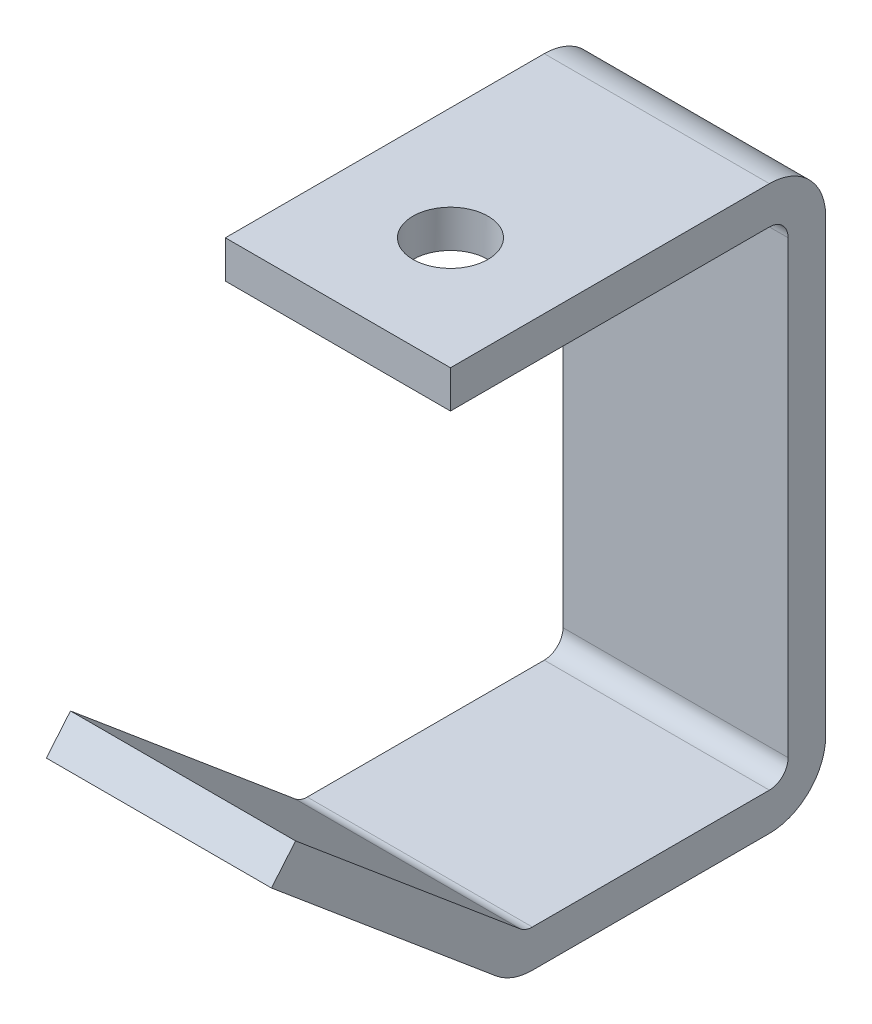
SolidWorks part; units mm, degrees
ref_plane "front" through (0, 0, 0) normal (0, 0, 1) x (1, 0, 0)
ref_plane "top" through (0, 0, 0) normal (0, 1, 0) x (1, 0, 0)
ref_plane "right" through (0, 0, 0) normal (1, 0, 0) x (0, 0, -1)
sketch "Sketch1" plane through (0, 0, 0) normal (1, 0, 0) x (0, 0, -1)
  line L0 (0, 0) -> (0, 82.55)
  line L1 (0, 82.55) -> (-57.15, 82.55)
  line L4 (-83.3651, 32.6536) -> (-44.45, 0)
  line L5 (-44.45, 0) -> (0, 0)
  dimension "D1" = 82.55
  dimension "D2" = 57.15
  dimension "D3" = 40
  dimension "D4" = 50.8
  dimension "D5" = 44.45
extrude "Base-Extrude-Thin" add sketch "Sketch1" along normal mid plane 38.1 thin
sketch "Sketch2" plane through (0, 88.9, 0) normal (0, 1, 0) x (-1, 0, 0)
  line L0 (0, 50) -> (0, -50) construction
  line L1 (-19.05, 57.15) -> (19.05, 57.15) construction
  circle A0 centre (0, 38.1) radius 6.35
  dimension "D1" = 12.7
  dimension "D2" = 19.05
extrude "Cut-Extrude1" cut sketch "Sketch2" against normal up to next
